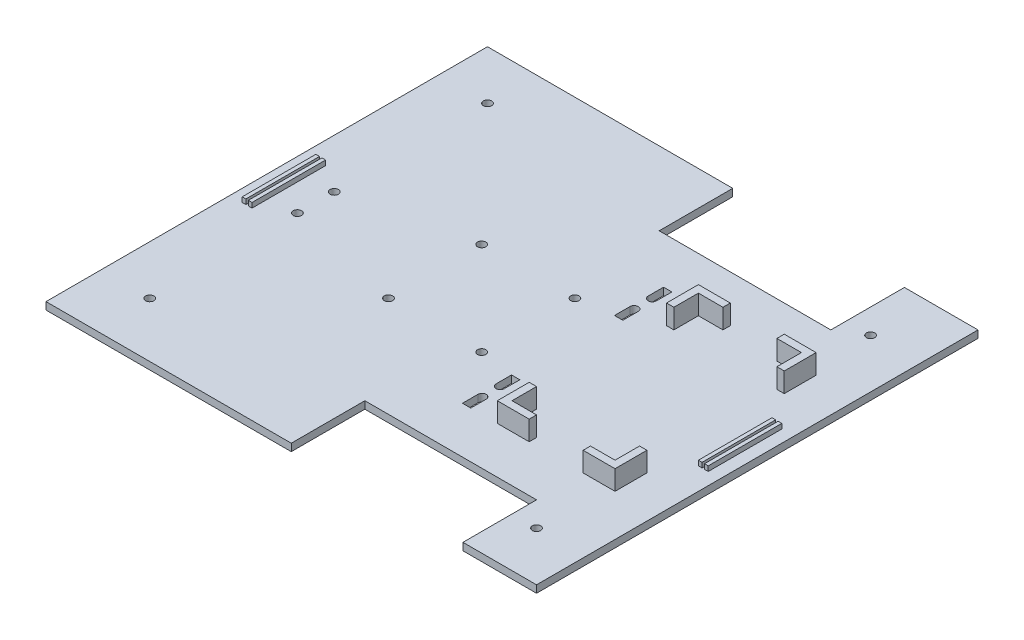
SolidWorks part; units mm, degrees
ref_plane "Front Plane" through (0, 0, 0) normal (0, 0, 1) x (1, 0, 0)
ref_plane "Top Plane" through (0, 0, 0) normal (0, 1, 0) x (1, 0, 0)
ref_plane "Right Plane" through (0, 0, 0) normal (1, 0, 0) x (0, 0, -1)
sketch "Sketch1" plane through (0, 0, 0) normal (0, 1, 0) x (1, 0, 0)
  line L0 (-48.9431, 29.6359) -> (1729.0569, 29.6359)
  line L1 (1729.0569, 29.6359) -> (1729.0569, -732.3641)
  line L2 (-48.9431, 29.6359) -> (-48.9431, -732.3641)
  line L3 (1729.0569, -732.3641) -> (2491.0569, -732.3641)
  line L4 (2491.0569, -732.3641) -> (2491.0569, 3839.6359)
  line L5 (2491.0569, 3839.6359) -> (1729.0569, 3839.6359)
  line L6 (1729.0569, 3839.6359) -> (1729.0569, 3077.6359)
  line L7 (1729.0569, 3077.6359) -> (-48.9431, 3077.6359)
  line L8 (-48.9431, 3077.6359) -> (-48.9431, 3839.6359)
  line L9 (-48.9431, 3839.6359) -> (-2588.9431, 3839.6359)
  line L10 (-2588.9431, 3839.6359) -> (-2588.9431, -732.3641)
  line L11 (-2588.9431, -732.3641) -> (-48.9431, -732.3641)
  line L19 (565.7369, 2435.0159) -> (565.7369, 2595.0359)
  line L20 (565.7369, 2595.0359) -> (479.3769, 2595.0359)
  line L21 (479.3769, 2595.0359) -> (479.3769, 2435.0159)
  line L23 (565.7369, 2247.0559) -> (565.7369, 2087.0359)
  line L24 (565.7369, 2087.0359) -> (479.3769, 2087.0359)
  line L25 (479.3769, 2087.0359) -> (479.3769, 2247.0559)
  line L26 (479.3769, 1020.2359) -> (479.3769, 860.2159)
  line L27 (565.7369, 1020.2359) -> (479.3769, 1020.2359)
  line L28 (565.7369, 860.2159) -> (565.7369, 1020.2359)
  line L30 (479.3769, 512.2359) -> (479.3769, 672.2559)
  line L31 (565.7369, 512.2359) -> (479.3769, 512.2359)
  line L32 (565.7369, 672.2559) -> (565.7369, 512.2359)
  circle A0 centre (-2080.9431, -166.5082) radius 43.18
  circle A1 centre (-2080.9431, 1744.1359) radius 43.18
  circle A2 centre (-2080.9431, 1363.1359) radius 43.18
  arc A3 (479.3769, 2435.0159) -> (565.7369, 2435.0159) centre (522.5569, 2435.0159) ccw
  arc A4 (565.7369, 2247.0559) -> (479.3769, 2247.0559) centre (522.5569, 2247.0559) ccw
  arc A5 (565.7369, 860.2159) -> (479.3769, 860.2159) centre (522.5569, 860.2159) cw
  arc A6 (479.3769, 672.2559) -> (565.7369, 672.2559) centre (522.5569, 672.2559) cw
  circle A7 centre (-2080.9431, 3331.6359) radius 43.18
  circle A8 centre (1983.0569, -224.3641) radius 43.18
  circle A9 centre (1983.0569, 3235.0991) radius 43.18
  circle A14 centre (-845.4562, 1071.0359) radius 43.18
  circle A15 centre (119.7438, 1071.0359) radius 43.18
  circle A16 centre (119.7438, 2036.2359) radius 43.18
  circle A17 centre (-845.4562, 2036.2359) radius 43.18
extrude "Boss-Extrude1" add sketch "Sketch1" along normal blind 76.2
sketch "Sketch2" plane through (0, 76.2, 0) normal (0, 1, 0) x (1, 0, 0)
  line L0 (2059.2569, 512.2359) -> (2059.2569, 842.4359)
  line L2 (1983.0569, 842.4359) -> (1983.0569, 588.4359)
  line L3 (1983.0569, 588.4359) -> (1729.0569, 588.4359)
  line L4 (840.0569, 842.4359) -> (916.2569, 842.4359)
  line L5 (1170.2569, 512.2359) -> (1170.2569, 588.4359)
  line L6 (840.0569, 512.2359) -> (1170.2569, 512.2359)
  line L8 (840.0569, 2595.0359) -> (840.0569, 2264.8359)
  line L9 (2059.2569, 512.2359) -> (1729.0569, 512.2359)
  line L10 (1729.0569, 512.2359) -> (1729.0569, 588.4359)
  line L11 (2059.2569, 842.4359) -> (1983.0569, 842.4359)
  line L12 (916.2569, 588.4359) -> (1170.2569, 588.4359)
  line L13 (916.2569, 842.4359) -> (916.2569, 588.4359)
  line L14 (840.0569, 512.2359) -> (840.0569, 842.4359)
  line L15 (916.2569, 2264.8359) -> (916.2569, 2518.8359)
  line L16 (916.2569, 2518.8359) -> (1170.2569, 2518.8359)
  line L17 (2059.2569, 2264.8359) -> (1983.0569, 2264.8359)
  line L18 (1729.0569, 2595.0359) -> (1729.0569, 2518.8359)
  line L19 (2059.2569, 2595.0359) -> (1729.0569, 2595.0359)
  line L20 (840.0569, 2595.0359) -> (1170.2569, 2595.0359)
  line L21 (1170.2569, 2595.0359) -> (1170.2569, 2518.8359)
  line L22 (840.0569, 2264.8359) -> (916.2569, 2264.8359)
  line L23 (1983.0569, 2518.8359) -> (1729.0569, 2518.8359)
  line L24 (1983.0569, 2264.8359) -> (1983.0569, 2518.8359)
  line L25 (2059.2569, 2595.0359) -> (2059.2569, 2264.8359)
extrude "Boss-Extrude4" add sketch "Sketch2" along normal blind 203.2
sketch "Sketch5" plane through (0, 76.2, 0) normal (0, 1, 0) x (1, 0, 0)
  line L0 (2300.5569, 1172.6359) -> (2300.5569, 1553.6359)
  line L2 (-2461.9431, 1553.6359) -> (-2461.9431, 1934.6359)
  line L3 (-2461.9431, 1934.6359) -> (-2423.8431, 1934.6359)
  line L4 (-2423.8431, 1934.6359) -> (-2423.8431, 1172.6359)
  line L5 (-2423.8431, 1172.6359) -> (-2461.9431, 1172.6359)
  line L6 (-2461.9431, 1172.6359) -> (-2461.9431, 1553.6359)
  line L7 (2262.4569, 1172.6359) -> (2300.5569, 1172.6359)
  line L8 (-2398.4431, 1553.6359) -> (-2398.4431, 1934.6359)
  line L9 (-2398.4431, 1934.6359) -> (-2360.3431, 1934.6359)
  line L10 (-2360.3431, 1934.6359) -> (-2360.3431, 1172.6359)
  line L11 (-2360.3431, 1172.6359) -> (-2398.4431, 1172.6359)
  line L12 (-2398.4431, 1172.6359) -> (-2398.4431, 1553.6359)
  line L14 (2262.4569, 1934.6359) -> (2262.4569, 1172.6359)
  line L15 (2300.5569, 1934.6359) -> (2262.4569, 1934.6359)
  line L16 (2300.5569, 1553.6359) -> (2300.5569, 1934.6359)
  line L17 (2364.0569, 1172.6359) -> (2364.0569, 1553.6359)
  line L18 (2325.9569, 1172.6359) -> (2364.0569, 1172.6359)
  line L19 (2325.9569, 1934.6359) -> (2325.9569, 1172.6359)
  line L20 (2364.0569, 1934.6359) -> (2325.9569, 1934.6359)
  line L21 (2364.0569, 1553.6359) -> (2364.0569, 1934.6359)
  point P0 (0, 0)
extrude "Boss-Extrude8" add sketch "Sketch5" along normal blind 50.8
